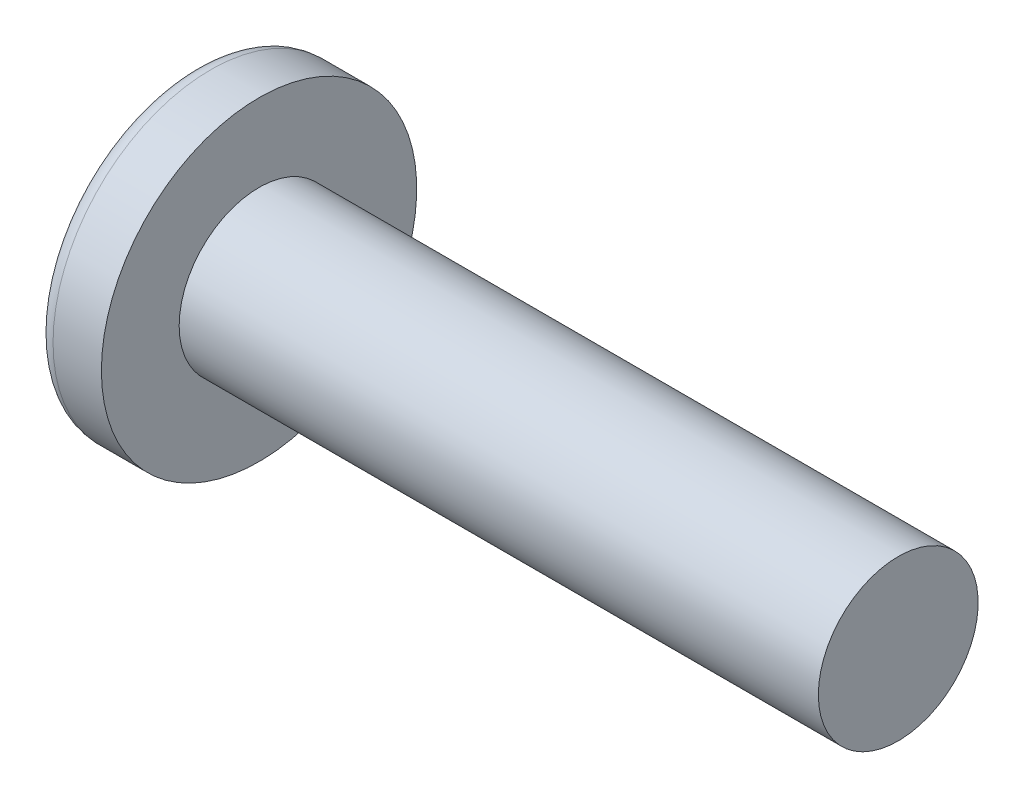
SolidWorks part; units mm, degrees
ref_plane "Plane1" through (0, 0, 0) normal (0, 0, 1) x (1, 0, 0)
ref_plane "Plane2" through (0, 0, 0) normal (0, 1, 0) x (1, 0, 0)
ref_plane "Plane3" through (0, 0, 0) normal (1, 0, 0) x (0, 0, -1)
sketch "BodySke" plane through (0, 0, 0) normal (0, 0, 1) x (1, 0, 0)
  line L0 (6.6294, 4.7625) -> (6.6294, 9.398)
  line L1 (7.4232, 6.35) -> (7.4232, -3.175) construction
  line L2 (-25.4, 0) -> (127, 0) construction
  line L3 (44.7294, 0) -> (0, 0)
  line L4 (6.6294, 4.7625) -> (44.7294, 4.7625)
  line L5 (44.7294, 4.7625) -> (44.7294, 0)
  line L6 (3.7481, 9.398) -> (6.6294, 9.398)
  line L7 (6.6294, -4.7625) -> (44.7294, -4.7625) construction
  line L8 (12.9794, 6.35) -> (12.9794, -3.175) construction
  arc A0 (2.9272, 8.9807) -> (0, 0) centre (15.24, 0) ccw
  arc A2 (2.9272, 8.9807) -> (3.7481, 9.398) centre (3.7481, 8.382) cw
  dimension "Head_crown_rad" = 15.24
  dimension "Head_fillet_rad" = 1.016
  dimension "Diameter" = 9.525
  dimension "Length" = 38.1
  dimension "Head_ht" = 6.6294
  dimension "Head_dia" = 18.796
  dimension "Advance" = 1.5875
  dimension "Thread_nom" = 31.75
revolve "Base-Revolve" add sketch "BodySke" angle 360 about L2
cosmetic thread "ThreadCosmetic" [suppressed] parameters "Thread_length"=31.75, "Thread_minor"=7.9375
sketch "Sketch3" plane through (0, 0, 0) normal (1, 0, 0) x (0, 0, -1)
  line L0 (1.0287, -6.096) -> (-1.0287, -6.096)
  line L1 (1.0287, -6.096) -> (1.0287, 6.096)
  line L2 (-1.0287, 6.096) -> (1.0287, 6.096)
  line L3 (-1.0287, 6.096) -> (-1.0287, -6.096)
  dimension "Cross_dia" = 12.192
  dimension "D1" = 6.096
  dimension "Cross_width" = 2.0574
  dimension "D2" = 1.0287
ref_plane "Plane4" through (7.2644, 0, 0) normal (1, 0, 0) x (0, 0, -1)
sketch "Sketch4" plane through (7.2644, 0, 0) normal (1, 0, 0) x (0, 0, -1)
  line L0 (0.5143, -0.5143) -> (-0.5143, -0.5144)
  line L1 (0.5143, -0.5143) -> (0.5143, 0.5143)
  line L2 (-0.5143, 0.5143) -> (0.5143, 0.5143)
  line L3 (-0.5143, 0.5143) -> (-0.5143, -0.5144)
  dimension "D2" = 1.0287
  dimension "D1" = 1.0287
  dimension "D3" = 0.5143
  dimension "D4" = 0.5143
loft "Cut-Loft1" cut profiles "Sketch3", "Sketch4"
pattern_circular "CirPattern1" count 2 every 90 about axis through (0, 0, 0) along (1, 0, 0) of "Cut-Loft1"
sketch "ThdSchSke" plane through (0, 0, 0) normal (0, 0, 1) x (1, 0, 0)
  line L0 (12.9794, -3.9688) -> (12.4236, -4.7625)
  line L1 (12.9794, -3.9688) -> (13.5352, -4.7625)
  line L2 (13.5352, -4.7625) -> (13.5352, -5.9531)
  line L3 (-3.175, 0) -> (5.1513, 0) construction
  line L5 (13.5352, -5.9531) -> (12.4236, -5.9531)
  line L6 (12.4236, -5.9531) -> (12.4236, -4.7625)
  dimension "Diameter" = 9.525
  dimension "SideAngle" = 55
  dimension "VeeAngle" = 70
  dimension "Thread_minor" = 7.9375
  dimension "Overcut" = 11.9063
  dimension "Start" = 12.9794
revolve "ThreadSchematic" [suppressed] cut sketch "ThdSchSke" angle 360 about L3
pattern_linear "ThdSchPat" [suppressed]
equation "\"D1@Sketch3\" = \"Cross_dia@Sketch3\" / 2"
equation "\"D2@Sketch3\" = \"Cross_width@Sketch3\" / 2"
equation "\"D1@Sketch4\" = \"Cross_width@Sketch3\" *.5"
equation "\"D2@Sketch4\" = \"D1@Sketch4\""
equation "\"D3@Sketch4\" = \"D1@Sketch4\" / 2"
equation "\"D4@Sketch4\" = \"D2@Sketch4\" / 2"
equation "\"Thread_length@ThreadCosmetic\" = ((sgn( (\"Length@BodySke\" - \"Advance@BodySke\" ) - \"Thread_nom@BodySke\" )-1)*( (\"Length@BodySke\" - \"Advance@BodySke\" ) - \"Thread_nom@BodySke\" ))/-2+ \"Thread_nom@BodySke\""
equation "\"Thread_minor@ThdSchSke\" = \"Thread_minor@ThreadCosmetic\""
equation "\"Diameter@ThdSchSke\" = \"Diameter@BodySke\""
equation "\"Overcut@ThdSchSke\" = \"Diameter@BodySke\" * 1.25"
equation "\"Start@ThdSchSke\" = \"Head_ht@BodySke\" + \"Length@BodySke\" - \"Thread_length@ThreadCosmetic\"  '---Non-countersunk---"
equation "\"Num_threads@ThdSchPat\" = int( \"Thread_length@ThreadCosmetic\" / \"Advance@BodySke\" + 0.999 )  + 1"
equation "\"Advance@ThdSchPat\" = \"Thread_length@ThreadCosmetic\" /  (\"Num_threads@ThdSchPat\" - 1) 'relax it"
